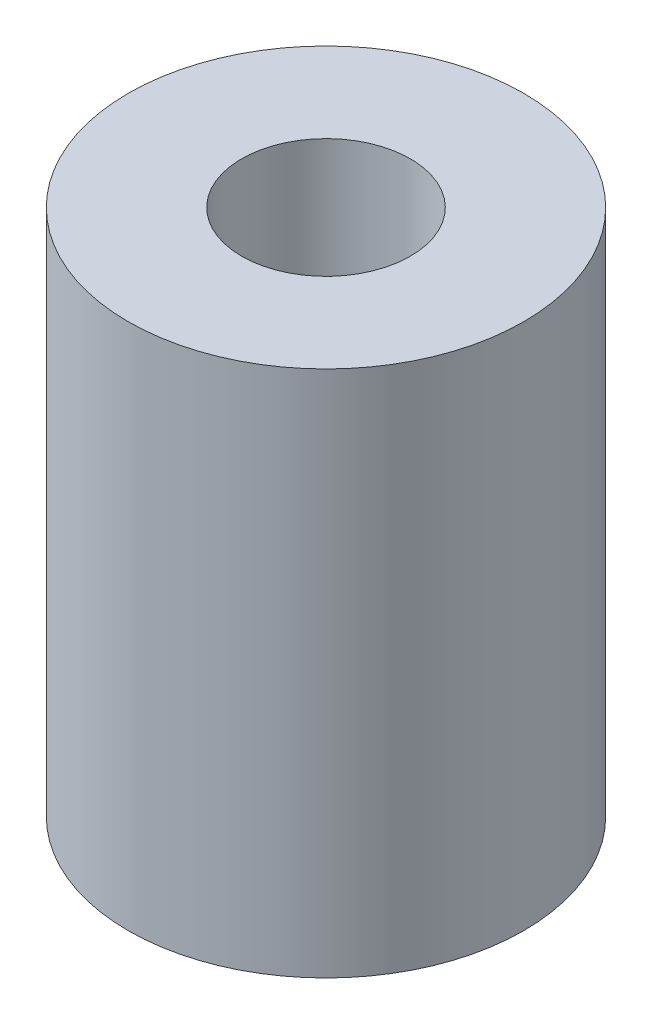
SolidWorks part; units mm, degrees
ref_plane "Front Plane" through (0, 0, 0) normal (0, 0, 1) x (1, 0, 0)
ref_plane "Top Plane" through (0, 0, 0) normal (0, 1, 0) x (1, 0, 0)
ref_plane "Right Plane" through (0, 0, 0) normal (1, 0, 0) x (0, 0, -1)
sketch "Sketch1" plane through (0, 0, 0) normal (0, 1, 0) x (1, 0, 0)
  circle A0 centre (0, 0) radius 4.7625
  circle A1 centre (0, 0) radius 2.032
  dimension "D1" = 9.525
  dimension "D2" = 4.064
extrude "Boss-Extrude1" add sketch "Sketch1" along normal blind 12.7
